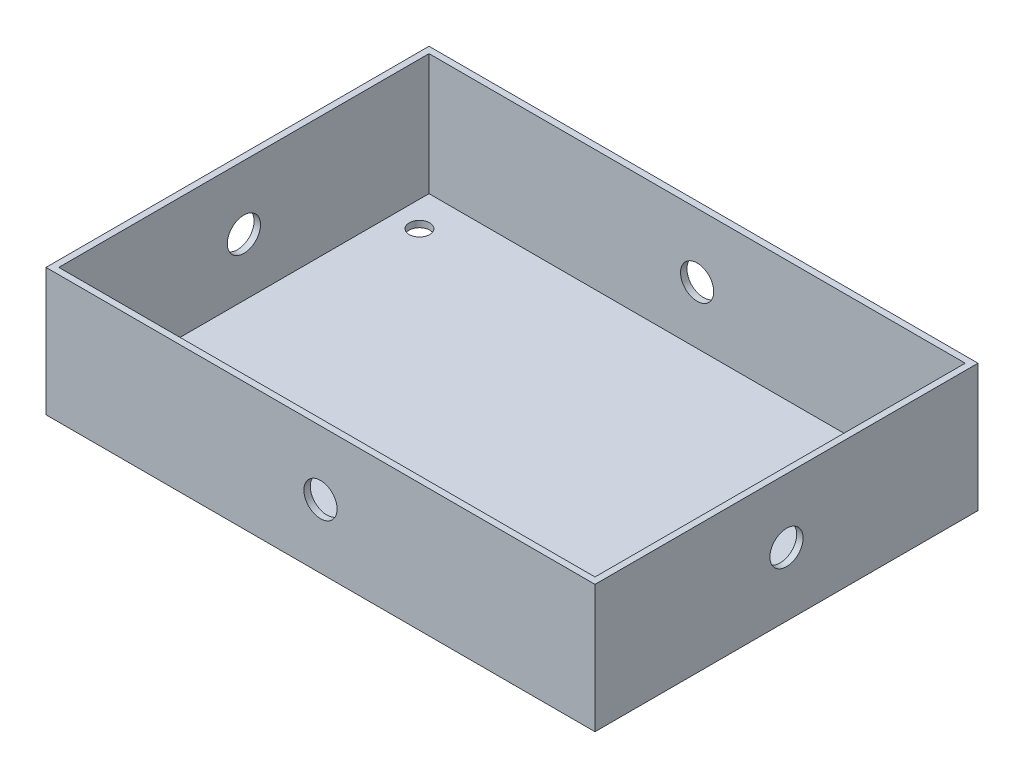
SolidWorks part; units mm, degrees
ref_plane "前视基准面" through (0, 0, 0) normal (0, 0, 1) x (1, 0, 0)
ref_plane "上视基准面" through (0, 0, 0) normal (0, 1, 0) x (1, 0, 0)
ref_plane "右视基准面" through (0, 0, 0) normal (1, 0, 0) x (0, 0, -1)
sketch "草图1" plane through (0, 0, 0) normal (0, 1, 0) x (1, 0, 0)
  line L1 (-43, -30) -> (43, -30)
  line L2 (-43, -30) -> (-43, 30)
  line L3 (-43, 30) -> (43, 30)
  line L4 (43, -30) -> (43, 30)
  line L5 (-43, -30) -> (43, 30) construction
  line L6 (-43, 30) -> (43, -30) construction
  point P0 (0, 0)
  dimension "D1" = 86
  dimension "D2" = 60
extrude "凸台-拉伸1" add sketch "草图1" along normal blind 20
sketch "草图2" plane through (0, 20, 0) normal (0, 1, 0) x (1, 0, 0)
  line L0 (43, 30) -> (-43, 30) construction
  line L1 (-42, 29) -> (42, 29)
  line L2 (-42, 29) -> (-42, -29)
  line L3 (-42, -29) -> (42, -29)
  line L4 (42, 29) -> (42, -29)
  line L5 (-42, 29) -> (42, -29) construction
  line L6 (-42, -29) -> (42, 29) construction
  line L7 (43, -30) -> (43, 30) construction
  point P0 (0, 0)
  dimension "D1" = 1
  dimension "D2" = 1
extrude "切除-拉伸1" cut sketch "草图2" against normal offset from surface (19 mm away) 1 up to face at (0, 0, 0)
sketch "草图3" plane through (0, 0, 0) normal (0, -1, 0) x (1, 0, 0)
  line L0 (0, 22.2827) -> (0, -17.0958) construction
  line L1 (-16.0228, 0) -> (24.7802, 0) construction
  circle A0 centre (-38, 23.5) radius 1.6
  circle A1 centre (38, 23.5) radius 1.6
  circle A2 centre (38, -23.5) radius 1.6
  circle A3 centre (-38, -23.5) radius 1.6
  dimension "D1" = 3.2
  dimension "D2" = 76
  dimension "D3" = 47
extrude "切除-拉伸2" cut sketch "草图3" against normal blind 1
sketch "草图4" plane through (-43, 0, 0) normal (-1, 0, 0) x (0, 0, 1)
  line L0 (-30, 10) -> (30, 10) construction
  line L1 (-30, 20) -> (-30, 0) construction
  line L2 (30, 20) -> (30, 0) construction
  circle A0 centre (0, 10) radius 2.6
  dimension "D1" = 5.2
extrude "切除-拉伸3" cut sketch "草图4" against normal through all
sketch "草图5" plane through (0, 0, -30) normal (0, 0, -1) x (-1, 0, 0)
  line L0 (-43, 10) -> (43, 10) construction
  line L1 (-43, 20) -> (-43, 0) construction
  line L2 (43, 20) -> (43, 0) construction
  circle A0 centre (0, 10) radius 2.6
  dimension "D1" = 5.2
extrude "切除-拉伸4" cut sketch "草图5" against normal through all
